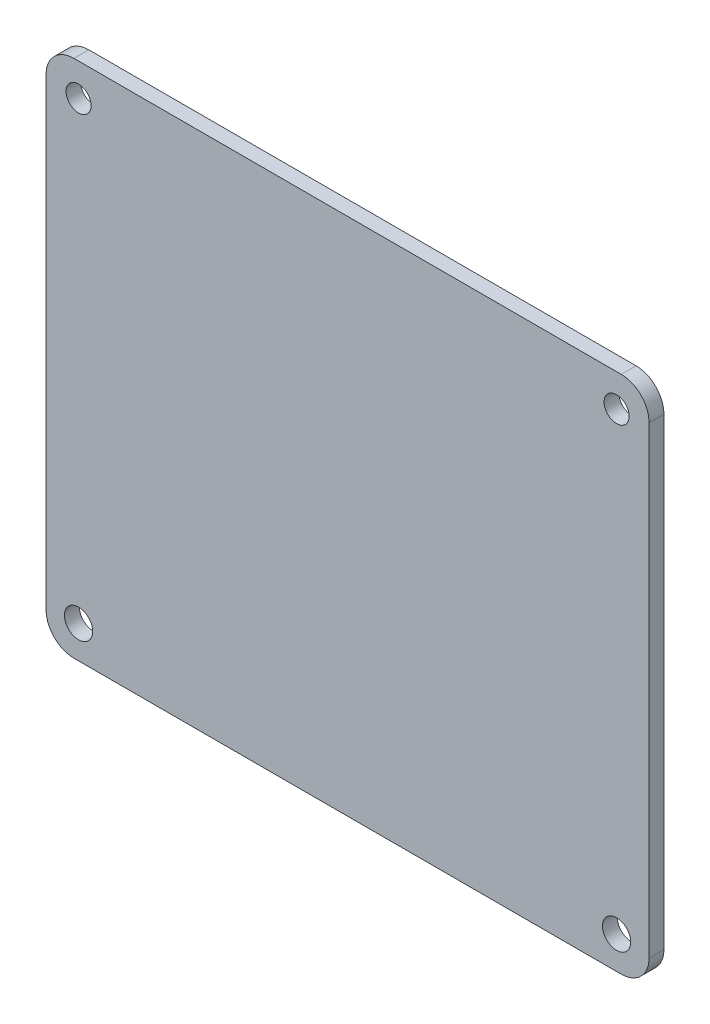
SolidWorks part; units mm, degrees
ref_plane "Front Plane" through (0, 0, 0) normal (0, 0, 1) x (1, 0, 0)
ref_plane "Top Plane" through (0, 0, 0) normal (0, 1, 0) x (1, 0, 0)
ref_plane "Right Plane" through (0, 0, 0) normal (1, 0, 0) x (0, 0, -1)
sketch "Sketch1" plane through (0, 0, 0) normal (0, 0, 1) x (1, 0, 0)
  line L0 (22.5, 25) -> (22.5, -25)
  line L1 (19, 24.5) -> (19.5, 25) construction
  line L2 (39.5, 28) -> (-39.5, 28) construction
  line L4 (42.5, -25) -> (42.5, 25)
  line L5 (39.5, 28) -> (-39.5, 28)
  line L6 (-42.5, 25) -> (-42.5, -25)
  line L7 (-39.5, -28) -> (39.5, -28)
  line L9 (19.5, 28) -> (-39.5, 28)
  line L10 (-42.5, 25) -> (-42.5, -25)
  line L11 (-39.5, -28) -> (19.5, -28)
  arc A0 (22.5, 25) -> (19.5, 28) centre (19.5, 25) ccw
  arc A1 (22.5, -25) -> (19.5, -28) centre (19.5, -25) cw
  circle A2 centre (19, 24.5) radius 1.35 construction
  circle A3 centre (-39, 24.5) radius 1.35 construction
  arc A4 (42.5, 25) -> (39.5, 28) centre (39.5, 25) ccw
  arc A5 (-39.5, 28) -> (-42.5, 25) centre (-39.5, 25) ccw
  arc A6 (-42.5, -25) -> (-39.5, -28) centre (-39.5, -25) ccw
  arc A7 (39.5, -28) -> (42.5, -25) centre (39.5, -25) ccw
  arc A9 (-39.5, 28) -> (-42.5, 25) centre (-39.5, 25) ccw
  arc A10 (-42.5, -25) -> (-39.5, -28) centre (-39.5, -25) ccw
  circle A11 centre (-39, -24.5) radius 1.524 construction
  circle A12 centre (19, -24.5) radius 1.524 construction
  circle A13 centre (-39, 24.5) radius 1.35
  circle A14 centre (-39, -24.5) radius 1.524
  circle A15 centre (19, -24.5) radius 1.524
  circle A16 centre (19, 24.5) radius 1.35
  point P18 (19, 24.5)
  dimension "D2" = 45
  dimension "D1" = 0
extrude "Boss-Extrude1" add sketch "Sketch1" along normal blind 1.6
